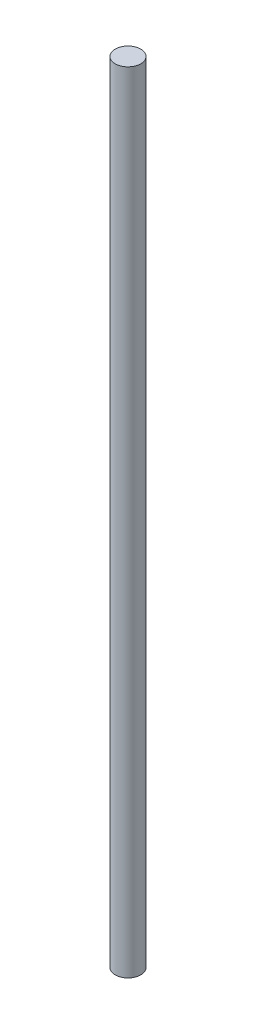
SolidWorks part; units mm, degrees
ref_plane "Front Plane" through (0, 0, 0) normal (0, 0, 1) x (1, 0, 0)
ref_plane "Top Plane" through (0, 0, 0) normal (0, 1, 0) x (1, 0, 0)
ref_plane "Right Plane" through (0, 0, 0) normal (1, 0, 0) x (0, 0, -1)
sketch "Sketch1" plane through (0, 0, 0) normal (0, 1, 0) x (1, 0, 0)
  circle A0 centre (0, 0) radius 1
  dimension "D1" = 2
extrude "Boss-Extrude1" add sketch "Sketch1" along normal blind 61.8
ref_plane "Plane1" through (1, 0, 0) normal (1, 0, 0) x (0, 0, -1)
